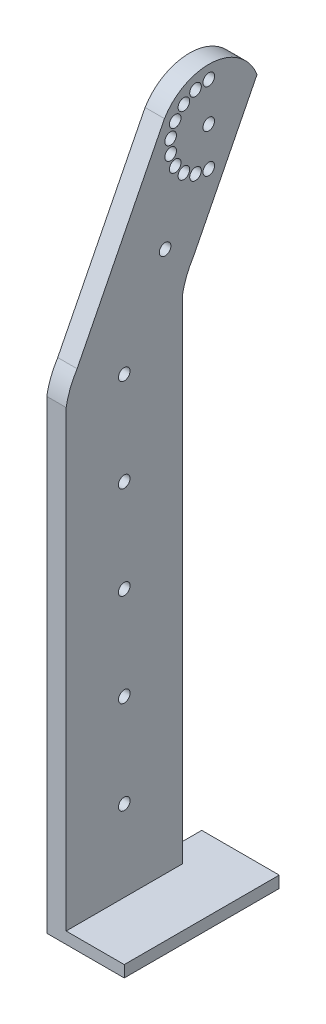
SolidWorks part; units mm, degrees
ref_plane "前视基准面" through (0, 0, 0) normal (0, 0, 1) x (1, 0, 0)
ref_plane "上视基准面" through (0, 0, 0) normal (0, 1, 0) x (1, 0, 0)
ref_plane "右视基准面" through (0, 0, 0) normal (1, 0, 0) x (0, 0, -1)
sketch "草图1" plane through (0, 0, 0) normal (1, 0, 0) x (0, 0, -1)
  line L0 (-15, 0) -> (15, 0)
  line L1 (-15, 0) -> (-15, 120)
  line L2 (15, 0) -> (15, 130)
  line L3 (17.8333, 137.2485) -> (34.2776, 169.8061)
  line L4 (-12.1667, 127.2485) -> (10.3753, 171.8787)
  line L5 (13.1525, 169.9179) -> (21.8127, 164.9179) construction
  line L7 (11.218, 143.9417) -> (10.5417, 142.6028) construction
  line L8 (21.8127, 164.9179) -> (15.3848, 172.5784) construction
  line L9 (21.8127, 164.9179) -> (11.9646, 166.6544) construction
  line L10 (11.9646, 163.1814) -> (21.8127, 164.9179) construction
  line L11 (21.8127, 164.9179) -> (18.3925, 155.521) construction
  line L12 (21.8127, 164.9179) -> (21.8127, 154.9179) construction
  line L13 (18.3925, 174.3148) -> (21.8127, 164.9179) construction
  line L14 (21.8127, 164.9179) -> (13.1525, 159.9179) construction
  line L15 (21.8127, 164.9179) -> (21.8127, 174.9179) construction
  line L16 (15.3848, 157.2575) -> (21.8127, 164.9179) construction
  arc A0 (15, 130) -> (17.8333, 137.2485) centre (34.6882, 126.4823) cw
  arc A1 (-12.1667, 127.2485) -> (-15, 120) centre (4.6882, 116.4823) ccw
  circle A2 centre (0, 23.9341) radius 1.5
  circle A3 centre (0, 47.9341) radius 1.5
  circle A4 centre (0, 71.9341) radius 1.5
  circle A5 centre (0, 95.9341) radius 1.5
  circle A7 centre (21.8127, 164.9179) radius 10 construction
  circle A8 centre (10.5417, 142.6028) radius 1.5
  circle A9 centre (0, 119.9341) radius 1.5
  arc A10 (34.2776, 169.8061) -> (10.3753, 171.8787) centre (21.8127, 164.9179) ccw
  circle A11 centre (21.8127, 164.9179) radius 1.5
  circle A13 centre (11.9646, 166.6544) radius 1.5
  circle A14 centre (11.9646, 163.1814) radius 1.5
  circle A15 centre (13.1525, 159.9179) radius 1.5
  circle A16 centre (15.3848, 157.2575) radius 1.5
  circle A19 centre (21.8127, 154.9179) radius 1.5
  circle A20 centre (18.3925, 155.521) radius 1.5
  circle A21 centre (13.1525, 169.9179) radius 1.5
  circle A22 centre (15.3848, 172.5784) radius 1.5
  circle A23 centre (18.3925, 174.3148) radius 1.5
  circle A24 centre (21.8127, 174.9179) radius 1.5
  point P3 (0, 0)
  dimension "D5" = 20
  dimension "D7" = 20
  dimension "D4" = 3
  dimension "D9" = 3
  dimension "D11" = 3
  dimension "D16" = 20
  dimension "D20" = 20
  dimension "D22" = 20
  dimension "D24" = 20
  dimension "D1" = 30
  dimension "D2" = 120
  dimension "D3" = 130
  dimension "D6" = 24
  dimension "D8" = 25
  dimension "D12" = 25
  dimension "D10" = 15
  dimension "D13" = 24
  dimension "D14" = 24
  dimension "D15" = 24
  dimension "D17" = 20
  dimension "D18" = 20
  dimension "D19" = 20
  dimension "D21" = 20
  dimension "D23" = 20
extrude "凸台-拉伸2" add sketch "草图1" against normal blind 5
ref_plane "基准面1" through (-5, 0, 0) normal (-1, 0, 0) x (0, 0, 1)
sketch "草图3" plane through (-5, 0, 0) normal (-1, 0, 0) x (0, 0, 1)
  line L25 (-10, 5) -> (10, 5)
  line L26 (-10, 130.4183) -> (-10, 5)
  line L27 (10, 5) -> (10, 119.5247)
  line L28 (-28.6572, 169.7687) -> (-13.4775, 139.7151)
  line L29 (7.8255, 124.7531) -> (-14.7389, 169.4276)
  line L30 (-10, 5) -> (10, 5)
  line L31 (-10, 130.4183) -> (-10, 5)
  line L32 (10, 5) -> (10, 119.5247)
  line L33 (-28.6572, 169.7687) -> (-13.4775, 139.7151)
  line L34 (7.8255, 124.7531) -> (-14.7389, 169.4276)
  arc A19 (10, 119.5247) -> (7.8255, 124.7531) centre (-4.6882, 116.4823) ccw
  arc A20 (-10, 130.4183) -> (-13.4775, 139.7151) centre (-34.6882, 126.4823) ccw
  arc A21 (-14.7389, 169.4276) -> (-28.6572, 169.7687) centre (-21.8127, 164.9179) ccw
  arc A22 (10, 119.5247) -> (7.8255, 124.7531) centre (-4.6882, 116.4823) ccw
  arc A23 (-10, 130.4183) -> (-13.4775, 139.7151) centre (-34.6882, 126.4823) ccw
  arc A24 (-14.7389, 169.4276) -> (-28.6572, 169.7687) centre (-21.8127, 164.9179) ccw
  dimension "D1" = 5
extrude "切除-拉伸2" cut sketch "草图3" against normal blind 1
ref_plane "基准面3" through (-30, 0, 0) normal (-1, 0, 0) x (0, 0, 1)
ref_plane "基准面4" through (0, 0, 0) normal (0, -1, 0) x (-1, 0, 0)
sketch "草图4" plane through (0, 0, 0) normal (0, -1, 0) x (-1, 0, 0)
  line L0 (5, -15) -> (-15, -15)
  line L1 (5, -15) -> (0, -15) construction
  line L2 (-15, -15) -> (-15, 25)
  line L3 (-15, 25) -> (5, 25)
  line L4 (5, 25) -> (5, -15)
  line L5 (5, -15) -> (5, 15) construction
  point P6 (0, 0)
  point P7 (5, -15)
  dimension "D1" = 20
  dimension "D2" = 40
  dimension "D3" = 20
extrude "凸台-拉伸3" add sketch "草图4" against normal blind 3
